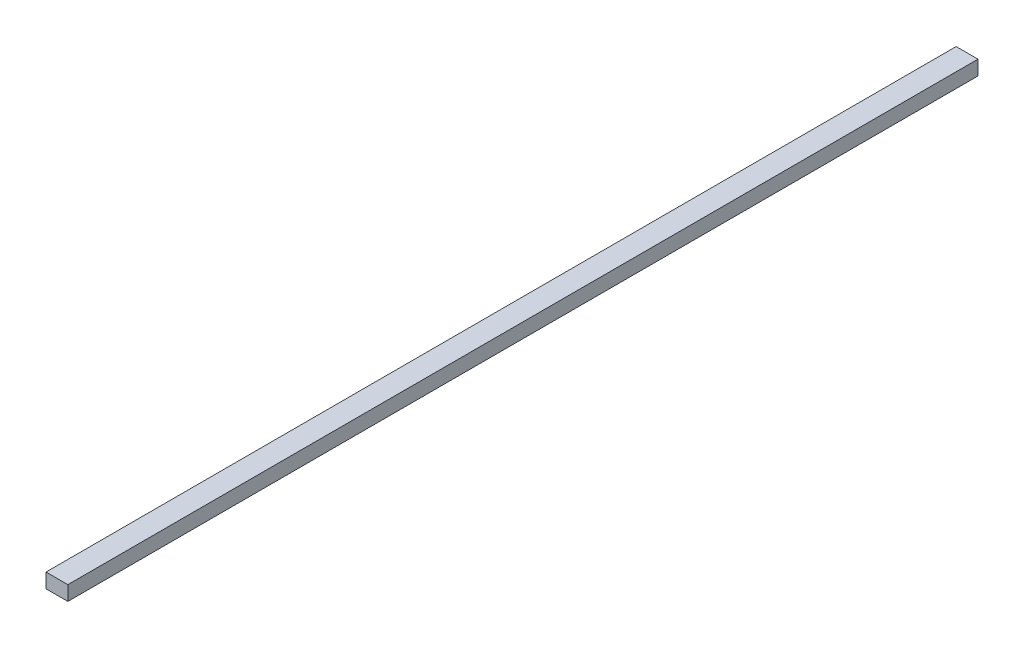
SolidWorks part; units mm, degrees
ref_plane "Front Plane" through (0, 0, 0) normal (0, 0, 1) x (1, 0, 0)
ref_plane "Top Plane" through (0, 0, 0) normal (0, 1, 0) x (1, 0, 0)
ref_plane "Right Plane" through (0, 0, 0) normal (1, 0, 0) x (0, 0, -1)
sketch "Sketch1" plane through (0, 0, 0) normal (0, 1, 0) x (1, 0, 0)
  line L1 (0, 0) -> (12, 0)
  line L2 (0, 0) -> (0, 500)
  line L3 (0, 500) -> (12, 500)
  line L4 (12, 0) -> (12, 500)
  dimension "D1" = 12
  dimension "D2" = 500
extrude "Boss-Extrude1" add sketch "Sketch1" along normal blind 8 contours L1 L4 L3 L2
